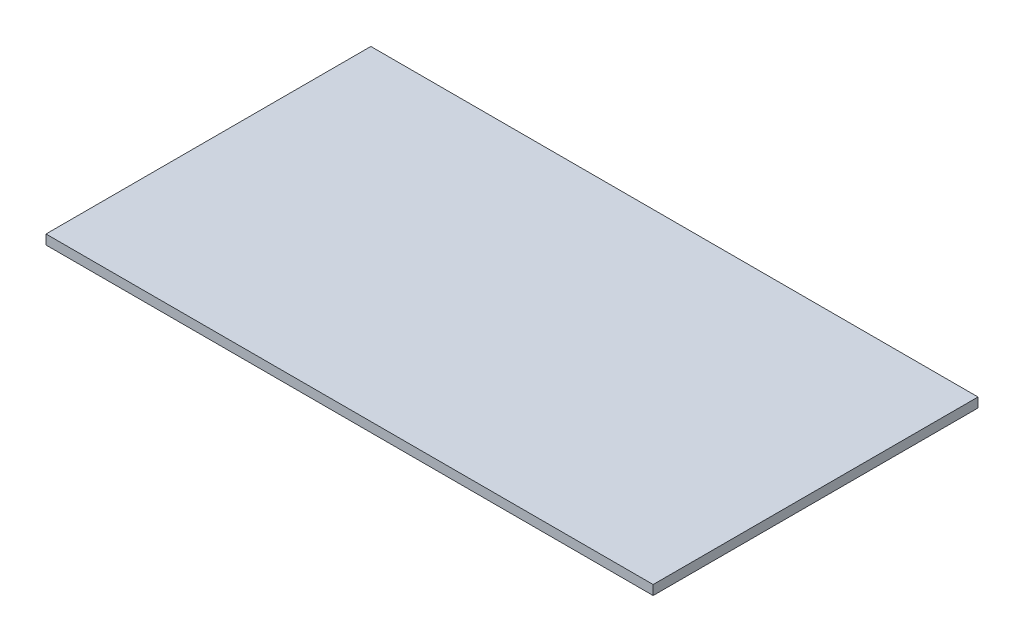
SolidWorks part; units mm, degrees
material "ABS"
ref_plane "Front" through (0, 0, 0) normal (0, 0, 1) x (1, 0, 0)
ref_plane "Top" through (0, 0, 0) normal (0, 1, 0) x (1, 0, 0)
ref_plane "Right" through (0, 0, 0) normal (1, 0, 0) x (0, 0, -1)
sketch "Sketch1" plane through (0, 0, 0) normal (0, 1, 0) x (1, 0, 0)
  line L0 (7.898, 4.24) -> (0, 4.24)
  line L1 (0, -4.24) -> (0, 4.24) construction
  line L2 (0, 4.24) -> (-7.952, 4.24)
  line L3 (-7.952, 4.24) -> (-7.952, -4.24)
  line L4 (-7.952, -4.24) -> (7.898, -4.24)
  line L5 (7.898, -4.24) -> (7.898, 4.24)
  point P6 (0, 0)
  dimension "D1" = 15.85
  dimension "D2" = 8.48
  dimension "D3" = 7.952
extrude "Boss-Extrude1" add sketch "Sketch1" along normal blind 0.25
